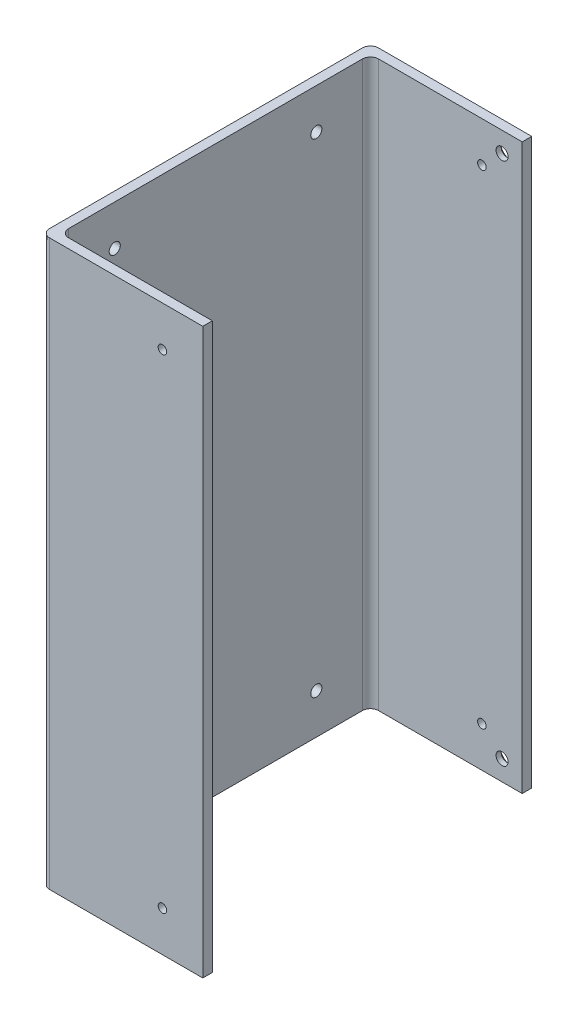
SolidWorks part; units mm, degrees
ref_plane "Front Plane" through (0, 0, 0) normal (0, 0, 1) x (1, 0, 0)
ref_plane "Top Plane" through (0, 0, 0) normal (0, 1, 0) x (1, 0, 0)
ref_plane "Right Plane" through (0, 0, 0) normal (1, 0, 0) x (0, 0, -1)
sketch "Sketch1" plane through (0, 0, 0) normal (0, 1, 0) x (1, 0, 0)
  line L0 (0, -2.54) -> (0, -101.092)
  line L1 (2.54, 0) -> (50.8, 0)
  line L2 (2.54, -103.632) -> (50.8, -103.632)
  line L3 (5.54, -100.632) -> (50.8, -100.632)
  line L4 (3, -5.54) -> (3, -98.092)
  line L5 (5.54, -3) -> (50.8, -3)
  line L6 (3, -3) -> (3, -100.632) construction
  line L7 (3, -3) -> (50.8, -3) construction
  line L8 (0, 0) -> (0, -103.632) construction
  line L9 (0, 0) -> (50.8, 0) construction
  line L10 (0, -103.632) -> (50.8, -103.632) construction
  line L11 (3, -100.632) -> (50.8, -100.632) construction
  line L12 (50.8, 0) -> (50.8, -3)
  line L13 (50.8, -100.632) -> (50.8, -103.632)
  arc A0 (3, -5.54) -> (5.54, -3) centre (5.54, -5.54) cw
  arc A1 (0, -2.54) -> (2.54, 0) centre (2.54, -2.54) cw
  arc A2 (0, -101.092) -> (2.54, -103.632) centre (2.54, -101.092) ccw
  arc A3 (5.54, -100.632) -> (3, -98.092) centre (5.54, -98.092) cw
  point P15 (0, 0)
  dimension "D4" = 2.54
  dimension "D1" = 103.632
  dimension "D2" = 50.8
  dimension "D3" = 3
extrude "Extrude1" add sketch "Sketch1" against normal blind 177.8
hole_wizard "#6-32 Tapped Hole1" positions "Sketch3" profile "Sketch2" tap size "#6-32" standard "Ansi Inch"
sketch "Sketch3" plane through (0, 0, 0) normal (-1, 0, 0) x (0, 0, 1)
  line L0 (103.632, -177.8) -> (103.632, 0) construction
  line L1 (2.54, 0) -> (101.092, 0) construction
  point P0 (20.066, -12.7)
  point P1 (83.566, -12.7)
  point P3 (83.566, -165.1)
  point P5 (20.066, -165.1)
  dimension "D1" = 152.4
  dimension "D2" = 63.5
  dimension "D3" = 20.066
  dimension "D4" = 12.7
sketch "Sketch2" plane through (0, -12.7, 20.066) normal (0, 1, 0) x (0, 0, 1)
  line L0 (0, 0) -> (0, 10.2005)
  line L1 (0, 10.2005) -> (1.3525, 9.3878)
  line L2 (1.3525, 9.3878) -> (1.3525, 7.0104)
  line L3 (1.3525, 7.0104) -> (1.7526, 7.0104)
  line L4 (1.7526, 7.0104) -> (1.7526, 0)
  line L5 (1.7526, 0) -> (0, 0)
  line L10 (0, 10.2005) -> (-1.3526, 9.3878) construction
  line L11 (0, -6.35) -> (0, 107.95) construction
  dimension "Tap Drill Dia." = 2.7051
  dimension "Tap Drill Depth" = 9.3878
  dimension "Thread Major Dia." = 3.5052
  dimension "Thread Depth" = 7.0104
  dimension "Drill Angle" = 118
hole_wizard "#6-32 Tapped Hole2" positions "Sketch5" profile "Sketch4" tap size "#6-32" standard "Ansi Inch"
sketch "Sketch5" plane through (0, 0, 0) normal (0, 0, -1) x (-1, 0, 0)
  point P0 (-38.1, -12.7)
  point P1 (-38.1, -165.1)
  dimension "D1" = 38.1
  dimension "D2" = 152.4
  dimension "D3" = 12.7
sketch "Sketch4" plane through (38.1, -12.7, 0) normal (1, 0, 0) x (0, 1, 0)
  line L0 (0, 0) -> (0, 10.2005)
  line L1 (0, 10.2005) -> (1.3525, 9.3878)
  line L2 (1.3525, 9.3878) -> (1.3525, 0)
  line L5 (1.3525, 0) -> (0, 0)
  line L10 (0, 10.2005) -> (-1.3526, 9.3878) construction
  line L11 (0, -6.35) -> (0, 107.95) construction
  dimension "Tap Drill Dia." = 2.7051
  dimension "Tap Drill Depth" = 9.3878
  dimension "Drill Angle" = 118
cosmetic thread "Hole Thread1" parameters "D1"=3, "D2"=3.5052
cosmetic thread "Hole Thread2" parameters "D1"=3, "D2"=3.5052
hole_wizard "#6-32 Tapped Hole3" positions "Sketch7" profile "Sketch6" tap size "#6-32" standard "Ansi Inch"
sketch "Sketch7" plane through (0, 0, 103.632) normal (0, 0, 1) x (1, 0, 0)
  point P0 (38.1, -12.7)
  point P1 (38.1, -165.1)
  dimension "D1" = 12.7
  dimension "D2" = 152.4
  dimension "D3" = 38.1
sketch "Sketch6" plane through (38.1, -12.7, 103.632) normal (1, 0, 0) x (0, -1, 0)
  line L0 (0, 0) -> (0, 10.2005)
  line L1 (0, 10.2005) -> (1.3525, 9.3878)
  line L2 (1.3525, 9.3878) -> (1.3525, 0)
  line L5 (1.3525, 0) -> (0, 0)
  line L10 (0, 10.2005) -> (-1.3525, 9.3878) construction
  line L11 (0, -6.35) -> (0, 107.95) construction
  dimension "Tap Drill Dia." = 2.7051
  dimension "Tap Drill Depth" = 9.3878
  dimension "Drill Angle" = 118
cosmetic thread "Hole Thread3" parameters "D1"=3, "D2"=3.5052
cosmetic thread "Hole Thread4" parameters "D1"=3, "D2"=3.5052
hole_wizard "CSK for #6 Flat Head Machine Screw (100)1" positions "Sketch9" profile "Sketch8" countersink size "#6" standard "Ansi Inch"
sketch "Sketch9" plane through (0, 0, 0) normal (0, 0, -1) x (-1, 0, 0)
  circle A0 centre (-38.1, -165.1) radius 1.3526 construction
  point P0 (-44.45, -171.45)
  point P1 (-44.45, -6.35)
  dimension "D2" = 6.35
  dimension "D3" = 6.35
  dimension "D1" = 165.1
sketch "Sketch8" plane through (44.45, -171.45, 0) normal (1, 0, 0) x (0, 1, 0)
  line L0 (0, 0) -> (0, 13.8408)
  line L1 (0, 13.8408) -> (1.8986, 12.7)
  line L2 (1.8986, 12.7) -> (1.8986, 1.38)
  line L3 (1.8986, 1.38) -> (3.5433, 0)
  line L5 (3.5433, 0) -> (0, 0)
  line L6 (-1.8986, 1.38) -> (-3.5433, 0) construction
  line L10 (0, 13.8408) -> (-1.8986, 12.7) construction
  line L11 (0, -6.35) -> (0, 107.95) construction
  dimension "Hole Dia." = 3.7973
  dimension "Hole Depth" = 12.7
  dimension "Near C'Sink Dia." = 7.0866
  dimension "Near C'Sink Angle" = 100
  dimension "Drill Angle" = 118
